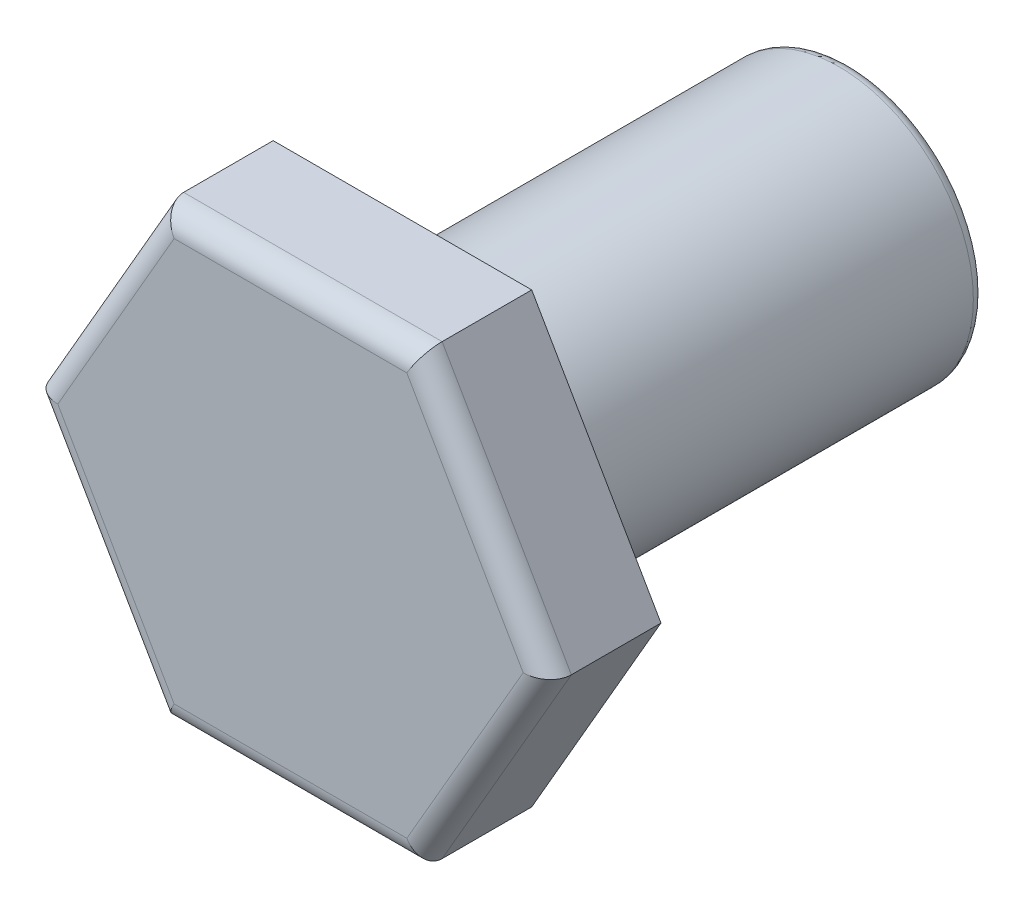
SolidWorks part; units mm, degrees
ref_plane "前视基准面" through (0, 0, 0) normal (0, 0, 1) x (1, 0, 0)
ref_plane "上视基准面" through (0, 0, 0) normal (0, 1, 0) x (1, 0, 0)
ref_plane "右视基准面" through (0, 0, 0) normal (1, 0, 0) x (0, 0, -1)
sketch "草图1" plane through (0, 0, 0) normal (0, 0, 1) x (1, 0, 0)
  circle A0 centre (0, 0) radius 6
  dimension "D1" = 12
extrude "凸台-拉伸1" add sketch "草图1" along normal blind 25
sketch "草图3" plane through (0, 0, 25) normal (0, 0, 1) x (1, 0, 0)
  line L1 (5.7735, -10) -> (11.547, 0)
  line L2 (11.547, 0) -> (5.7735, 10)
  line L3 (5.7735, 10) -> (-5.7735, 10)
  line L4 (-5.7735, 10) -> (-11.547, 0)
  line L5 (-11.547, 0) -> (-5.7735, -10)
  line L6 (-5.7735, -10) -> (5.7735, -10)
  circle A0 centre (0, 0) radius 10 construction
  dimension "D1" = 20
extrude "凸台-拉伸2" add sketch "草图3" against normal blind 5
fillet "圆角1" radius 1 6 edges at (8.6603, -5, 25) (0, -10, 25) (-8.6603, -5, 25) (-8.6603, 5, 25) (0, 10, 25) (8.6603, 5, 25)
fillet "圆角2" radius 0.5 1 edges at (6, 0, 0)
